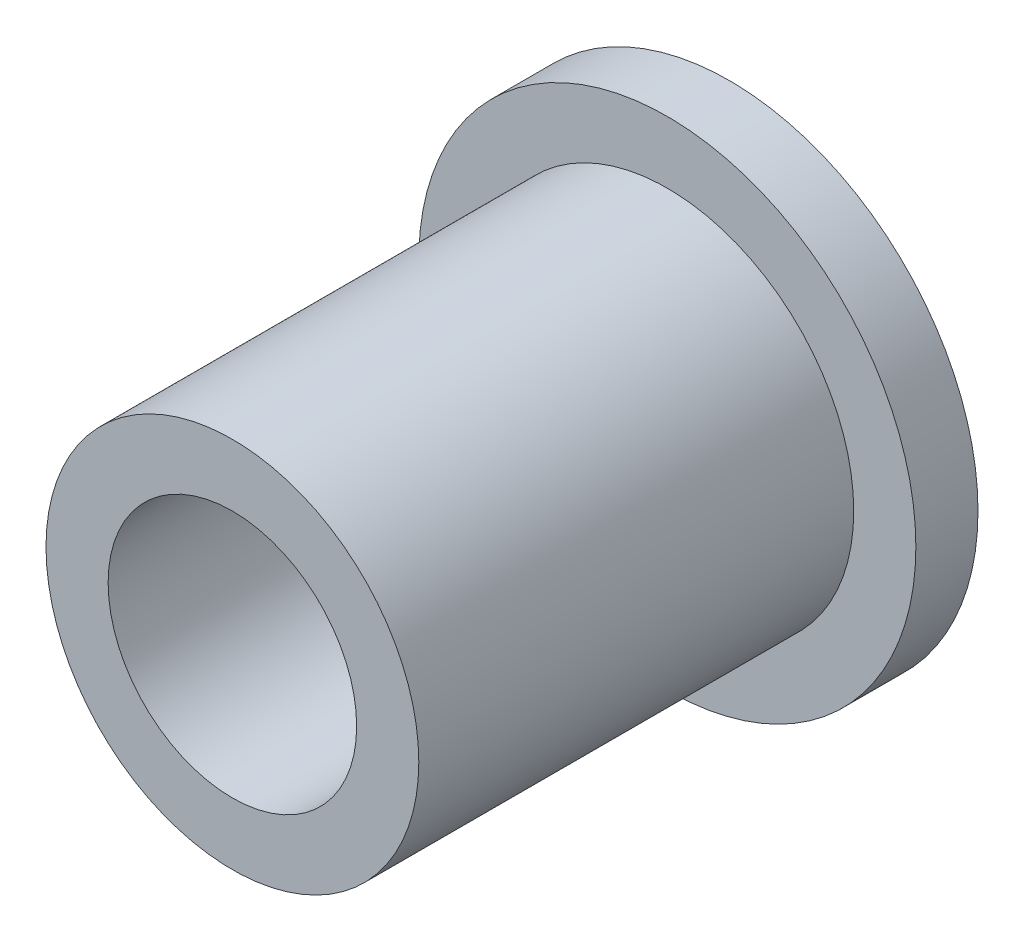
SolidWorks part; units mm, degrees
material "Commercial Bronze, UNS C22000 (90-10 Bronze)"
ref_plane "Front Plane" through (0, 0, 0) normal (0, 0, 1) x (1, 0, 0)
ref_plane "Top Plane" through (0, 0, 0) normal (0, 1, 0) x (1, 0, 0)
ref_plane "Right Plane" through (0, 0, 0) normal (1, 0, 0) x (0, 0, -1)
sketch "Sketch1" plane through (0, 0, 0) normal (1, 0, 0) x (0, 0, -1)
  line L0 (0, 3.175) -> (0, 4.7625)
  line L1 (0, 4.7625) -> (11.1125, 4.7625)
  line L2 (11.1125, 4.7625) -> (11.1125, 6.35)
  line L3 (11.1125, 6.35) -> (12.7, 6.35)
  line L4 (12.7, 6.35) -> (12.7, 3.175)
  line L5 (12.7, 3.175) -> (0, 3.175)
  line L6 (0, 0) -> (163.3728, 0) construction
  dimension "D1" = 6.35
  dimension "D2" = 9.525
  dimension "D3" = 12.7
  dimension "D4" = 12.7
  dimension "D5" = 1.5875
revolve "Revolve1" add sketch "Sketch1" angle 360 about L6
